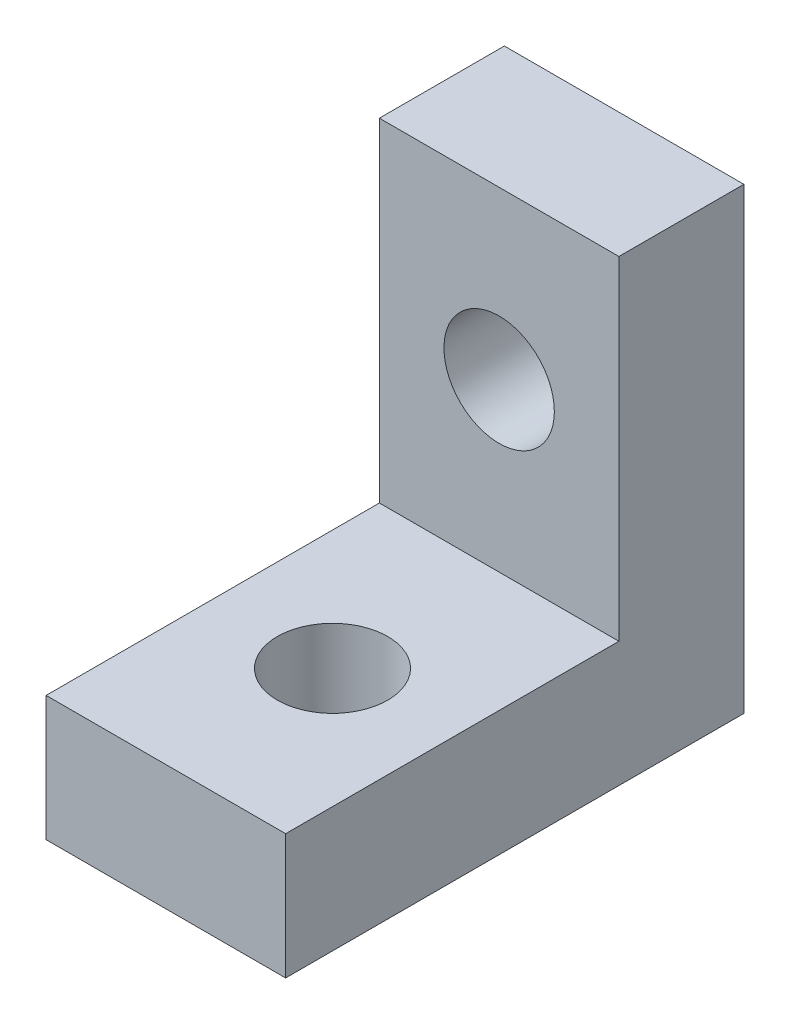
SolidWorks part; units mm, degrees
ref_plane "Front Plane" through (0, 0, 0) normal (0, 0, 1) x (1, 0, 0)
ref_plane "Top Plane" through (0, 0, 0) normal (0, 1, 0) x (1, 0, 0)
ref_plane "Right Plane" through (0, 0, 0) normal (1, 0, 0) x (0, 0, -1)
sketch "Sketch1" plane through (0, 0, 0) normal (1, 0, 0) x (0, 0, -1)
  line L0 (0, 0) -> (22, 0)
  line L1 (22, 0) -> (22, 22)
  line L2 (22, 22) -> (16, 22)
  line L3 (16, 22) -> (16, 6)
  line L4 (16, 6) -> (0, 6)
  line L5 (0, 6) -> (0, 0)
  dimension "D1" = 22
  dimension "D2" = 16
  dimension "D3" = 22
  dimension "D4" = 6
extrude "Boss-Extrude1" add sketch "Sketch1" against normal blind 11.5
sketch "Sketch2" plane through (0, 6, 0) normal (0, 1, 0) x (1, 0, 0)
  circle A0 centre (-5.75, 8) radius 2.65
  dimension "D1" = 5.3
sketch "Sketch3" plane through (0, 0, -16) normal (0, 0, 1) x (1, 0, 0)
  circle A0 centre (-5.75, 14) radius 2.65
  dimension "D1" = 5.3
extrude "Cut-Extrude1" cut sketch "Sketch2" against normal through all
extrude "Cut-Extrude2" cut sketch "Sketch3" against normal through all
